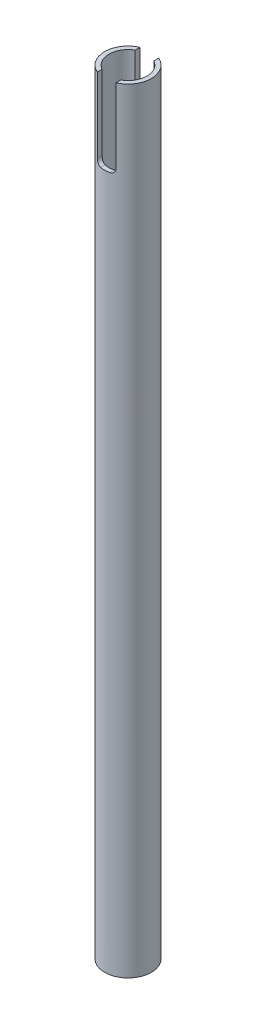
SolidWorks part; units mm, degrees
material "AISI 4130 Steel, normalized at 870C"
ref_plane "X-Y Datum" through (0, 0, 0) normal (0, 0, 1) x (1, 0, 0)
ref_plane "X-Z Datum" through (0, 0, 0) normal (0, 1, 0) x (1, 0, 0)
ref_plane "Y-Z Datum" through (0, 0, 0) normal (1, 0, 0) x (0, 0, -1)
sketch "Sketch1" plane through (0, 0, 0) normal (0, 1, 0) x (1, 0, 0)
  circle A0 centre (0, 0) radius 6.4643
  circle A1 centre (0, 0) radius 7.9375
  dimension "D1" = 1.4732
  dimension "D2" = 15.875
extrude "Boss-Extrude1" add sketch "Sketch1" along normal offset from surface (263.281 mm away) 25.4 from surface at -123.3946
sketch "Sketch2" plane through (0, 0, 0) normal (0, 0, 1) x (1, 0, 0)
  line L0 (0, 139.8865) -> (0, 112.899) construction
  line L1 (-3.175, 139.8865) -> (3.175, 139.8865)
  line L2 (-3.175, 139.8865) -> (-3.175, 114.4865)
  line L3 (-1.5875, 112.899) -> (1.5875, 112.899)
  line L4 (3.175, 139.8865) -> (3.175, 114.4865)
  line L6 (6.4643, 139.8865) -> (-6.4643, 139.8865) construction
  line L7 (-3.175, 144.9665) -> (-3.175, 117.6615) construction
  arc A0 (-3.175, 114.4865) -> (-1.5875, 112.899) centre (-1.5875, 114.4865) ccw
  arc A1 (1.5875, 112.899) -> (3.175, 114.4865) centre (1.5875, 114.4865) ccw
  dimension "D1" = 1.5875
extrude "Cut-Extrude2" cut sketch "Sketch2" against normal through all both and the other way through all
